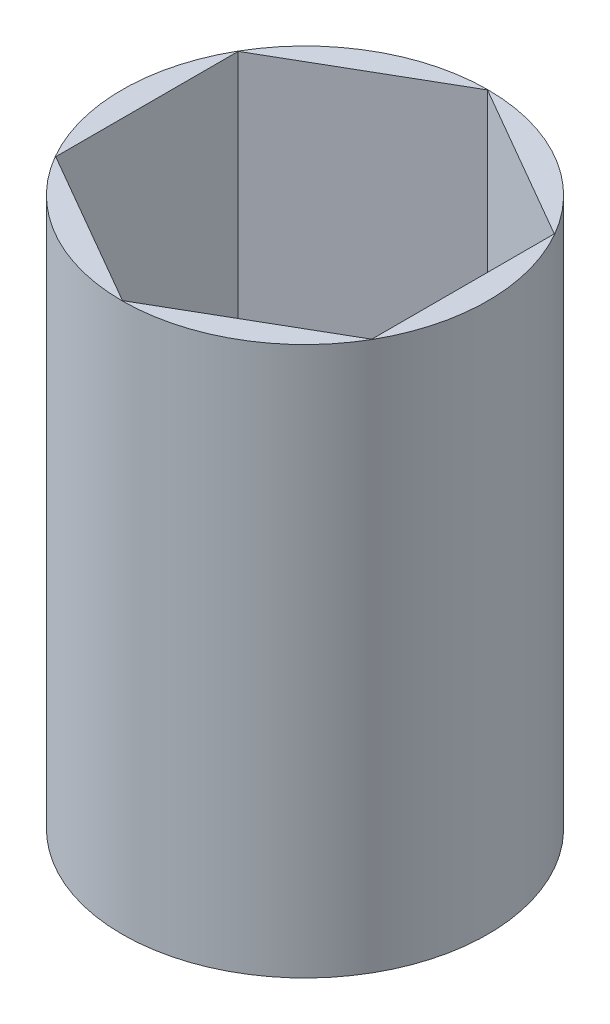
SolidWorks part; units mm, degrees
ref_plane "Front Plane" through (0, 0, 0) normal (0, 0, 1) x (1, 0, 0)
ref_plane "Top Plane" through (0, 0, 0) normal (0, 1, 0) x (1, 0, 0)
ref_plane "Right Plane" through (0, 0, 0) normal (1, 0, 0) x (0, 0, -1)
sketch "Sketch1" plane through (0, 0, 0) normal (0, 1, 0) x (1, 0, 0)
  line L1 (0, 6.9859) -> (-6.05, 3.493)
  line L2 (-6.05, 3.493) -> (-6.05, -3.493)
  line L3 (-6.05, -3.493) -> (0, -6.9859)
  line L4 (0, -6.9859) -> (6.05, -3.493)
  line L5 (6.05, -3.493) -> (6.05, 3.493)
  line L6 (6.05, 3.493) -> (0, 6.9859)
  circle A0 centre (0, 0) radius 6.05 construction
  circle A1 centre (0, 0) radius 7
  dimension "D2" = 14
  dimension "D1" = 12.1
extrude "Boss-Extrude1" add sketch "Sketch1" along normal blind 20
sketch "Sketch2" plane through (0, 0, 0) normal (0, -1, 0) x (1, 0, 0)
  circle A0 centre (0, 0) radius 2.05
  circle A1 centre (0, 0) radius 7
  dimension "D1" = 4.1
extrude "Boss-Extrude2" add sketch "Sketch2" along normal blind 1
